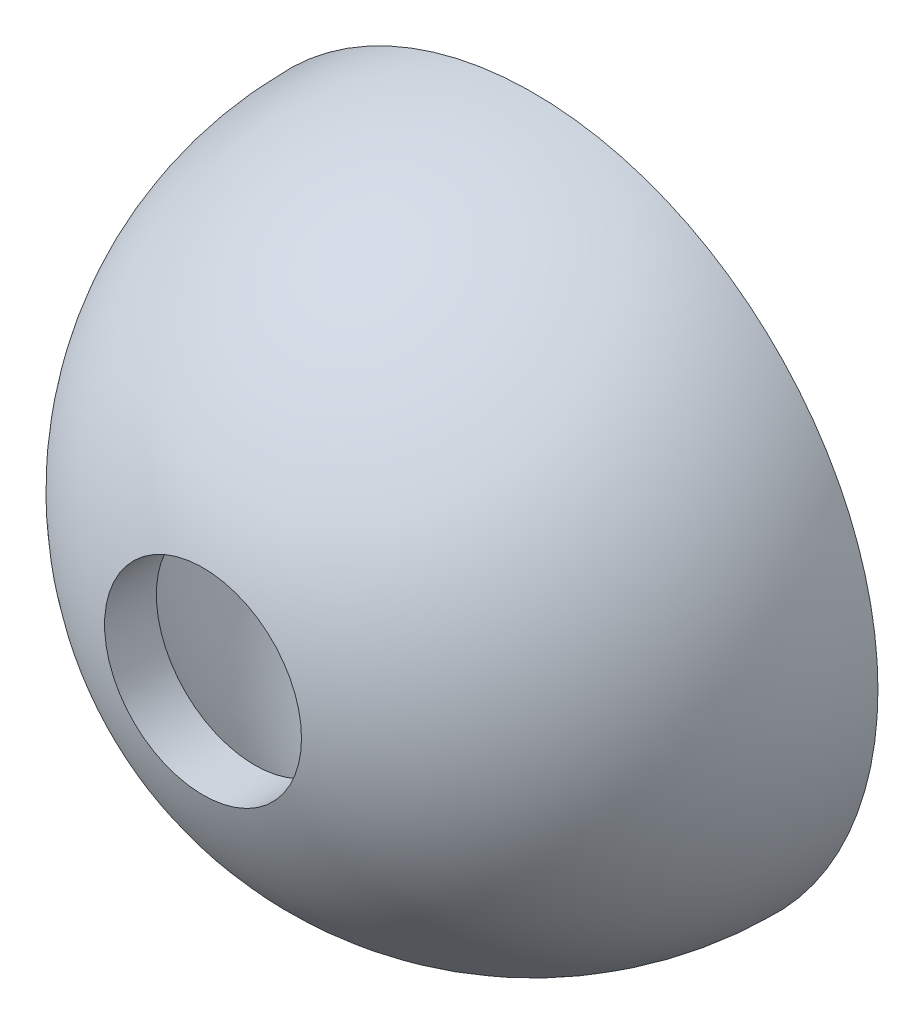
SolidWorks part; units mm, degrees
ref_plane "Front Plane" through (0, 0, 0) normal (0, 0, 1) x (1, 0, 0)
ref_plane "Top Plane" through (0, 0, 0) normal (0, 1, 0) x (1, 0, 0)
ref_plane "Right Plane" through (0, 0, 0) normal (1, 0, 0) x (0, 0, -1)
sketch "Sketch2" plane through (0, 0, 0) normal (0, 1, 0) x (1, 0, 0)
  line L0 (0, -12.3791) -> (0, -7) construction
  line L1 (7, 0) -> (6, 0)
  line L5 (2, -5.6569) -> (2, -6.7082)
  line L8 (0, -2.5) -> (0, 21.5618) construction
  arc A1 (2, -6.7082) -> (7, 0) centre (0, 0) ccw
  arc A2 (2, -5.6569) -> (6, 0) centre (0, 0) ccw
  point P7 (0.4488, -0.9679)
  point P9 (0, 0)
  dimension "D1" = 2
  dimension "D2" = 7
  dimension "D3" = 6
revolve "Revolve1" add sketch "Sketch2" angle 360 about L0
